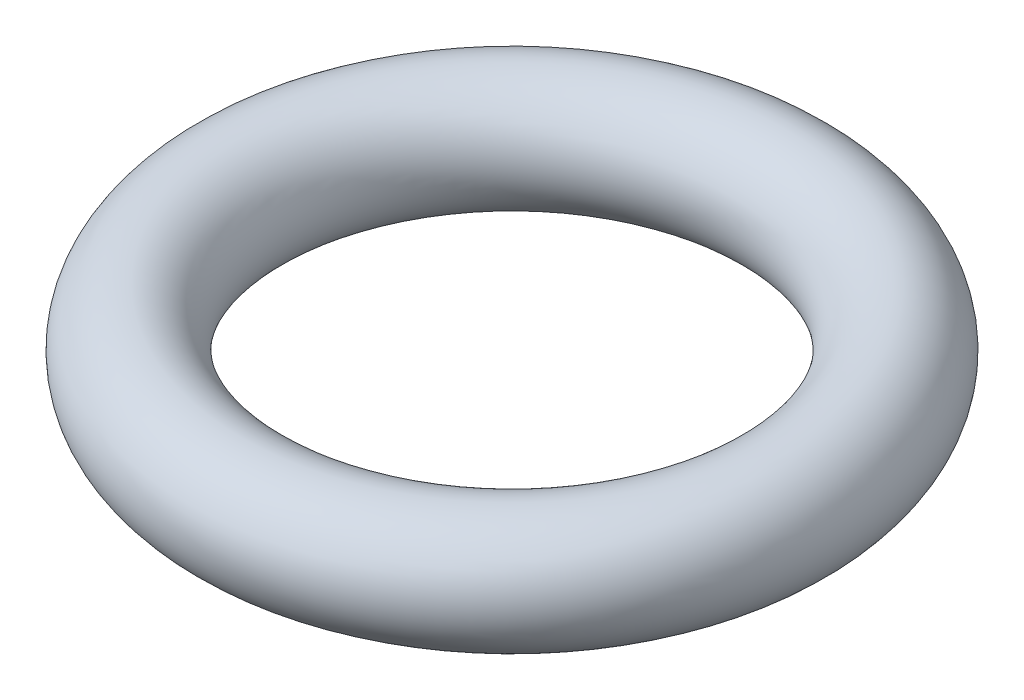
SolidWorks part; units mm, degrees
ref_plane "Front Plane" through (0, 0, 0) normal (0, 0, 1) x (1, 0, 0)
ref_plane "Top Plane" through (0, 0, 0) normal (0, 1, 0) x (1, 0, 0)
ref_plane "Right Plane" through (0, 0, 0) normal (1, 0, 0) x (0, 0, -1)
sketch "Sketch1" plane through (0, 0, 0) normal (0, 0, 1) x (1, 0, 0)
  line L0 (0, -5.3118) -> (0, 9.8848) construction
  circle A0 centre (13.1219, 0) radius 2.8197
revolve "Revolve1" add sketch "Sketch1" angle 360 about L0
sketch "Sketch2" plane through (0, 0, 0) normal (0, 1, 0) x (1, 0, 0)
  circle A0 centre (0, 0) radius 23.3083
